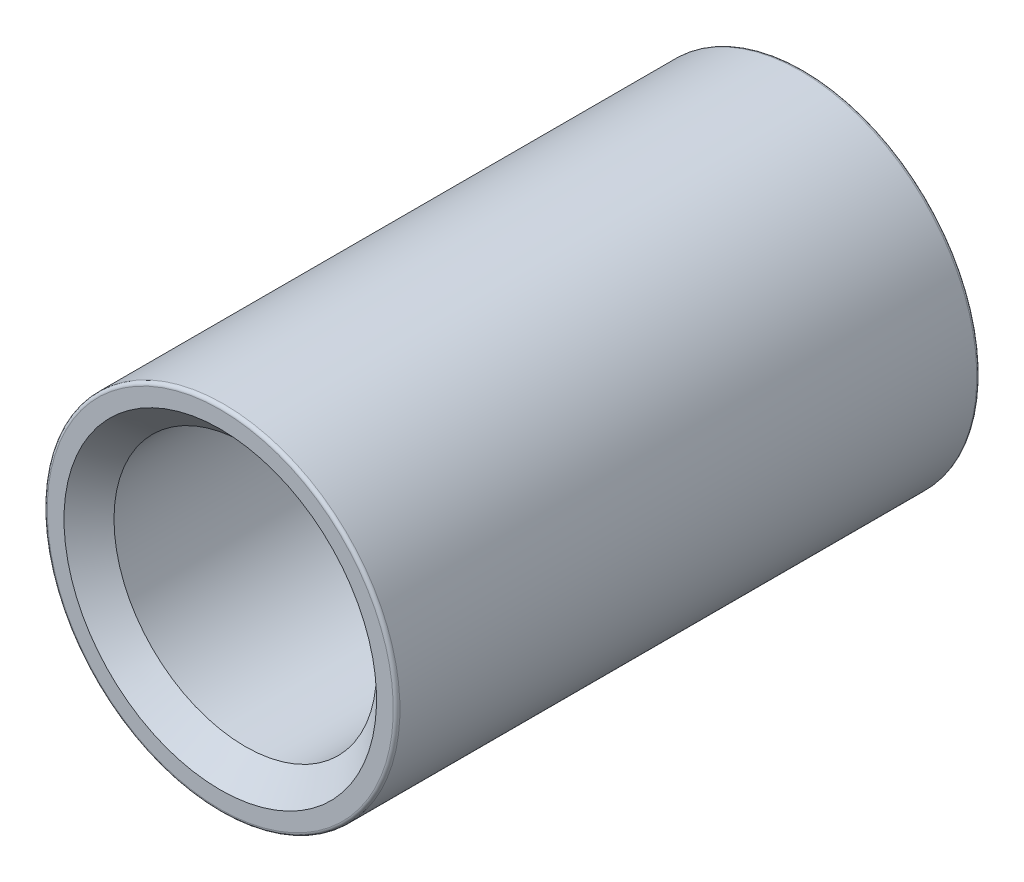
SolidWorks part; units mm, degrees
material "ABS"
ref_plane "Front Plane" through (0, 0, 0) normal (0, 0, 1) x (1, 0, 0)
ref_plane "Top Plane" through (0, 0, 0) normal (0, 1, 0) x (1, 0, 0)
ref_plane "Right Plane" through (0, 0, 0) normal (1, 0, 0) x (0, 0, -1)
sketch "Sketch2" plane through (0, 0, 0) normal (1, 0, 0) x (0, 0, -1)
  line L0 (-32.295, 9.374) -> (-32.295, 10.3791)
  line L1 (-32.095, 10.5791) -> (2.505, 10.5791)
  line L2 (2.705, 10.3791) -> (2.705, 0)
  line L3 (2.705, 0) -> (0, 0)
  line L4 (0, 0) -> (0, 7.874)
  line L5 (0, 7.874) -> (-30.795, 7.874)
  line L6 (-30.795, 7.874) -> (-32.295, 9.374)
  arc A0 (2.505, 10.5791) -> (2.705, 10.3791) centre (2.505, 10.3791) cw
  arc A1 (-32.295, 10.3791) -> (-32.095, 10.5791) centre (-32.095, 10.3791) cw
  point P0 (-32.295, 7.874)
  point P9 (2.705, 10.5791)
  point P12 (-32.295, 10.5791)
  dimension "D6" = 0.2
  dimension "D1" = 10.5791
  dimension "D2" = 7.874
  dimension "D3" = 35
  dimension "D4" = 2.705
  dimension "D5" = 2.7051
revolve "Revolve1" add sketch "Sketch2" angle 360 about L3
